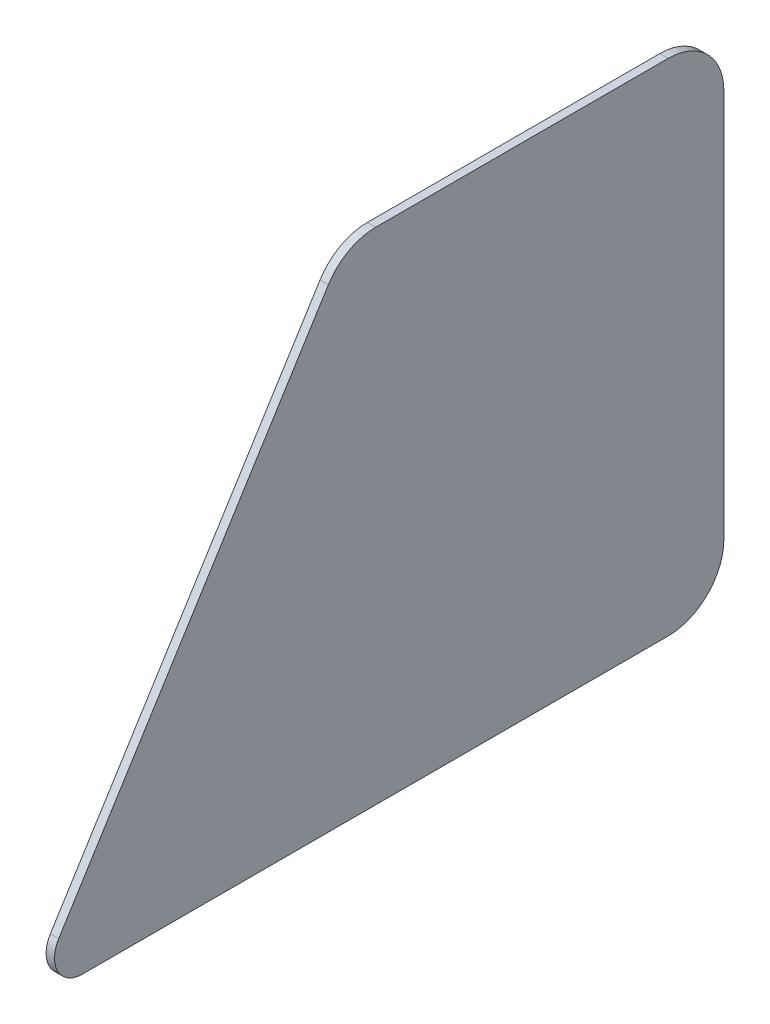
SolidWorks part; units mm, degrees
material "Acrylic (Medium-high impact)"
ref_plane "Front Plane" through (0, 0, 0) normal (0, 0, 1) x (1, 0, 0)
ref_plane "Top Plane" through (0, 0, 0) normal (0, 1, 0) x (1, 0, 0)
ref_plane "Right Plane" through (0, 0, 0) normal (1, 0, 0) x (0, 0, -1)
sketch "Sketch1" plane through (0, 0, 0) normal (1, 0, 0) x (0, 0, -1)
  line L0 (0, -1000) -> (0, 49000) construction
  line L1 (-1000, 0) -> (49000, 0) construction
  line L6 (-105.1013, 0) -> (105.1013, 0)
  line L7 (125.1013, 20) -> (125.1013, 159.5)
  line L8 (0.1286, 179.5) -> (105.1013, 179.5)
  line L9 (-16.8313, 170.1) -> (-113.5813, 15.3)
  arc A4 (-113.5813, 15.3) -> (-105.1013, 0) centre (-105.1013, 10) ccw
  arc A5 (105.1013, 0) -> (125.1013, 20) centre (105.1013, 20) ccw
  arc A6 (125.1013, 159.5) -> (105.1013, 179.5) centre (105.1013, 159.5) ccw
  arc A7 (0.1286, 179.5) -> (-16.8313, 170.1) centre (0.1286, 159.5) ccw
  point P4 (0, 0)
  point P6 (0, 0)
  point P7 (0, 0)
  point P18 (0, 0)
  dimension "D2" = 20
  dimension "D3" = 10
  dimension "D1" = 139.5
  dimension "D4" = 104.9727
  dimension "D5" = 182.5475
  dimension "D6" = 105.1013
  dimension "D7" = 40
  dimension "D8" = 125.1013
  dimension "D9" = 179.5
  dimension "D10" = 10
  dimension "D11" = 57.995
extrude "Boss-Extrude1" add sketch "Sketch1" along normal blind 3
